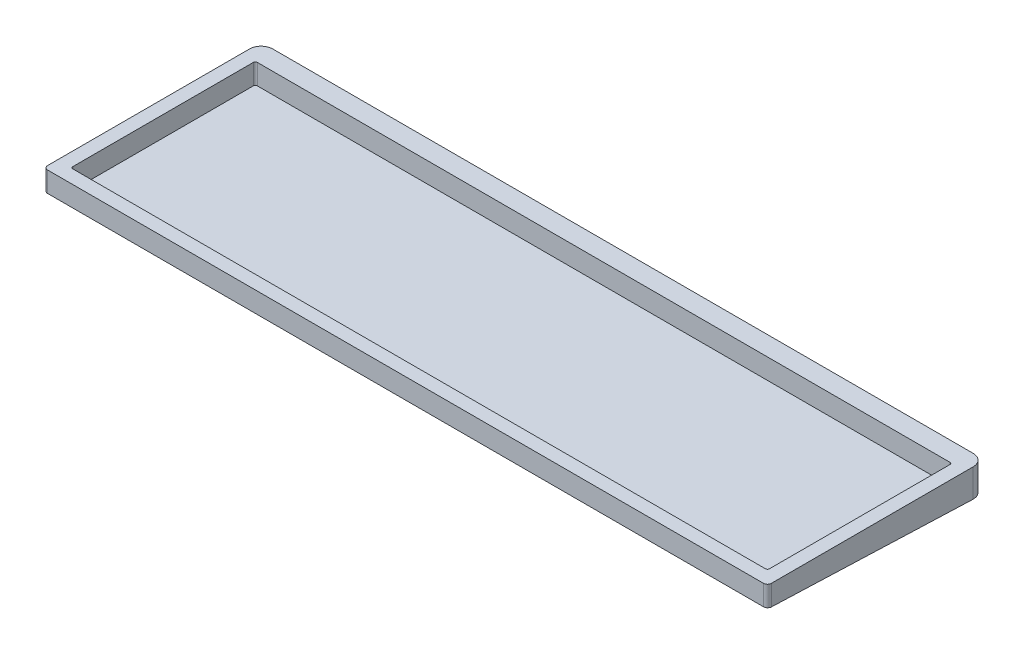
SolidWorks part; units mm, degrees
ref_plane "Front Plane" through (0, 0, 0) normal (0, 0, 1) x (1, 0, 0)
ref_plane "Top Plane" through (0, 0, 0) normal (0, 1, 0) x (1, 0, 0)
ref_plane "Right Plane" through (0, 0, 0) normal (1, 0, 0) x (0, 0, -1)
sketch "Sketch1" plane through (0, 0, 0) normal (0, 1, 0) x (1, 0, 0)
  line L1 (-178.825, 47.625) -> (178.825, 47.625)
  line L2 (-179.825, 46.625) -> (-179.825, -46.625)
  line L3 (-178.825, -47.625) -> (178.825, -47.625)
  line L4 (179.825, 46.625) -> (179.825, -46.625)
  line L5 (-179.825, 47.625) -> (179.825, -47.625) construction
  line L6 (-179.825, -47.625) -> (179.825, 47.625) construction
  arc A0 (178.825, -47.625) -> (179.825, -46.625) centre (178.825, -46.625) ccw
  arc A1 (178.825, 47.625) -> (179.825, 46.625) centre (178.825, 46.625) cw
  arc A2 (-179.825, -46.625) -> (-178.825, -47.625) centre (-178.825, -46.625) ccw
  arc A3 (-178.825, 47.625) -> (-179.825, 46.625) centre (-178.825, 46.625) ccw
  circle A4 centre (157.075, 19.175) radius 1.1
  circle A5 centre (136.925, -16.775) radius 1.1
  circle A6 centre (-153.475, 33.725) radius 1.1
  circle A7 centre (17.925, 22.275) radius 1.1
  circle A8 centre (17.875, -35.075) radius 1.1
  circle A9 centre (-130.375, -35.725) radius 1.1
  point P0 (0, 0)
  dimension "D3" = 1
  dimension "D4" = 2.2
  dimension "D7" = 2.2
  dimension "D8" = 2.2
  dimension "D9" = 2.2
  dimension "D10" = 2.2
  dimension "D11" = 2.2
  dimension "D1" = 359.65
  dimension "D2" = 95.25
  dimension "D5" = 22.75
  dimension "D6" = 28.45
  dimension "D12" = 42.9
  dimension "D13" = 30.85
  dimension "D14" = 25.35
  dimension "D15" = 161.9
  dimension "D16" = 12.55
  dimension "D17" = 161.95
  dimension "D18" = 11.9
  dimension "D19" = 49.45
  dimension "D20" = 13.9
  dimension "D21" = 26.35
sketch "Sketch2" plane through (0, 0, 0) normal (0, 1, 0) x (1, 0, 0)
  line L0 (-179.825, 46.625) -> (-179.825, -46.625) construction
  line L1 (-178.825, -47.625) -> (178.825, -47.625) construction
  line L2 (179.825, 46.625) -> (179.825, -46.625) construction
  line L3 (-178.825, 47.625) -> (178.825, 47.625) construction
  line L4 (-179.825, 46.625) -> (-179.825, -46.625)
  line L5 (-178.825, -47.625) -> (178.825, -47.625)
  line L6 (179.825, 46.625) -> (179.825, -46.625)
  line L7 (-178.825, 47.625) -> (178.825, 47.625)
  line L9 (-180.825, 57.625) -> (180.825, 57.625)
  line L10 (-186.825, 51.625) -> (-186.825, -52.625)
  line L11 (-184.825, -54.625) -> (184.825, -54.625)
  line L12 (186.825, 51.625) -> (186.825, -52.625)
  circle A0 centre (157.075, 19.175) radius 1.1 construction
  circle A1 centre (136.925, -16.775) radius 1.1 construction
  circle A2 centre (17.875, -35.075) radius 1.1 construction
  circle A3 centre (17.925, 22.275) radius 1.1 construction
  circle A4 centre (-153.475, 33.725) radius 1.1 construction
  circle A5 centre (-130.375, -35.725) radius 1.1 construction
  arc A6 (-179.825, -46.625) -> (-178.825, -47.625) centre (-178.825, -46.625) ccw construction
  arc A7 (178.825, -47.625) -> (179.825, -46.625) centre (178.825, -46.625) ccw construction
  arc A8 (179.825, 46.625) -> (178.825, 47.625) centre (178.825, 46.625) ccw construction
  arc A9 (-178.825, 47.625) -> (-179.825, 46.625) centre (-178.825, 46.625) ccw construction
  circle A10 centre (157.075, 19.175) radius 1.1
  circle A11 centre (136.925, -16.775) radius 1.1
  circle A12 centre (17.875, -35.075) radius 1.1
  circle A13 centre (17.925, 22.275) radius 1.1
  circle A14 centre (-153.475, 33.725) radius 1.1
  circle A15 centre (-130.375, -35.725) radius 1.1
  arc A16 (-179.825, -46.625) -> (-178.825, -47.625) centre (-178.825, -46.625) ccw
  arc A17 (178.825, -47.625) -> (179.825, -46.625) centre (178.825, -46.625) ccw
  arc A18 (179.825, 46.625) -> (178.825, 47.625) centre (178.825, 46.625) ccw
  arc A19 (-178.825, 47.625) -> (-179.825, 46.625) centre (-178.825, 46.625) ccw
  arc A20 (180.825, 57.625) -> (186.825, 51.625) centre (180.825, 51.625) cw
  arc A21 (-180.825, 57.625) -> (-186.825, 51.625) centre (-180.825, 51.625) ccw
  arc A22 (184.825, -54.625) -> (186.825, -52.625) centre (184.825, -52.625) ccw
  arc A23 (-186.825, -52.625) -> (-184.825, -54.625) centre (-184.825, -52.625) ccw
  point P30 (0, 0)
  dimension "D5" = 6
  dimension "D6" = 2
  dimension "D1" = 10
  dimension "D2" = 7
  dimension "D3" = 7
  dimension "D4" = 7
extrude "Boss-Extrude1" add sketch "Sketch2" along normal blind 10.5 contours L10 A23 L11 A22 L12 A20 L9 A21 A19 L7 A18 L6 A17 L5 A16 L4
sketch "Sketch4" plane through (0, 0, 0) normal (0, -1, 0) x (1, 0, 0)
  line L0 (186.825, -51.625) -> (186.825, 52.625) construction
  line L1 (-180.825, -57.625) -> (180.825, -57.625) construction
  line L2 (-186.825, -51.625) -> (-186.825, 52.625) construction
  line L3 (-184.825, 54.625) -> (184.825, 54.625) construction
  line L4 (-179.825, 46.625) -> (-179.825, -46.625)
  line L5 (178.825, 47.625) -> (-178.825, 47.625)
  line L6 (179.825, -46.625) -> (179.825, 46.625)
  line L7 (-178.825, -47.625) -> (178.825, -47.625)
  line L8 (-179.825, 46.625) -> (-179.825, -46.625)
  line L10 (179.825, -46.625) -> (179.825, 46.625)
  line L11 (-178.825, -47.625) -> (178.825, -47.625)
  line L12 (186.825, -51.625) -> (186.825, 52.625)
  line L13 (-180.825, -57.625) -> (180.825, -57.625)
  line L14 (-186.825, -51.625) -> (-186.825, 52.625)
  line L15 (-184.825, 54.625) -> (184.825, 54.625)
  arc A0 (186.825, 52.625) -> (184.825, 54.625) centre (184.825, 52.625) ccw construction
  arc A1 (180.825, -57.625) -> (186.825, -51.625) centre (180.825, -51.625) ccw construction
  arc A2 (-186.825, -51.625) -> (-180.825, -57.625) centre (-180.825, -51.625) ccw construction
  arc A3 (-184.825, 54.625) -> (-186.825, 52.625) centre (-184.825, 52.625) ccw construction
  arc A4 (-179.825, -46.625) -> (-178.825, -47.625) centre (-178.825, -46.625) ccw
  arc A5 (-178.825, 47.625) -> (-179.825, 46.625) centre (-178.825, 46.625) ccw
  arc A6 (179.825, 46.625) -> (178.825, 47.625) centre (178.825, 46.625) ccw
  arc A7 (178.825, -47.625) -> (179.825, -46.625) centre (178.825, -46.625) ccw
  arc A8 (-179.825, -46.625) -> (-178.825, -47.625) centre (-178.825, -46.625) ccw
  arc A9 (-178.825, 47.625) -> (-179.825, 46.625) centre (-178.825, 46.625) ccw
  arc A10 (179.825, 46.625) -> (178.825, 47.625) centre (178.825, 46.625) ccw
  arc A11 (178.825, -47.625) -> (179.825, -46.625) centre (178.825, -46.625) ccw
  arc A12 (186.825, 52.625) -> (184.825, 54.625) centre (184.825, 52.625) ccw
  arc A13 (180.825, -57.625) -> (186.825, -51.625) centre (180.825, -51.625) ccw
  arc A14 (-186.825, -51.625) -> (-180.825, -57.625) centre (-180.825, -51.625) ccw
  arc A15 (-184.825, 54.625) -> (-186.825, 52.625) centre (-184.825, 52.625) ccw
  arc M9 (-178.825, -47.625) -> (-179.825, -46.625) centre (-178.825, -46.625) cw
  line M10 (-179.825, -46.625) -> (-179.825, 46.625)
  arc M11 (-179.825, 46.625) -> (-178.825, 47.625) centre (-178.825, 46.625) cw
  line M12 (-178.825, 47.625) -> (178.825, 47.625)
  arc M13 (178.825, 47.625) -> (179.825, 46.625) centre (178.825, 46.625) cw
  line M14 (179.825, 46.625) -> (179.825, -46.625)
  arc M15 (179.825, -46.625) -> (178.825, -47.625) centre (178.825, -46.625) cw
  line M16 (178.825, -47.625) -> (-178.825, -47.625)
  line M17 (-186.825, 52.625) -> (-186.825, -51.625)
  arc M18 (-186.825, -51.625) -> (-180.825, -57.625) centre (-180.825, -51.625) ccw
  line M19 (-180.825, -57.625) -> (180.825, -57.625)
  arc M20 (180.825, -57.625) -> (186.825, -51.625) centre (180.825, -51.625) ccw
  line M21 (186.825, -51.625) -> (186.825, 52.625)
  arc M22 (186.825, 52.625) -> (184.825, 54.625) centre (184.825, 52.625) ccw
  line M23 (184.825, 54.625) -> (-184.825, 54.625)
  arc M24 (-184.825, 54.625) -> (-186.825, 52.625) centre (-184.825, 52.625) ccw
  dimension "D1" = 0
extrude "Boss-Extrude3" add sketch "Sketch4" along normal blind 10.5 contours M24 M17 M18 M19 M20 M21 M22 M23 M16 M9 M10 M11 M12 M13 M14 M15 | M9 M16 M15 M14 M13 M12 M11 M10
sketch "Sketch5" plane through (186.825, 0, 0) normal (1, 0, 0) x (0, 0, -1)
  line L0 (-54.625, 0) -> (57.625, 0) construction
  line L1 (-54.625, 10.5) -> (-54.625, -10.5) construction
  line L2 (57.625, 10.5) -> (57.625, -10.5) construction
  line L4 (57.625, -4) -> (51.625, -4)
  line L14 (40.9479, -10.5) -> (-54.625, 0)
  line L17 (-54.625, 0) -> (-54.625, -10.5)
  line L18 (-54.625, -10.5) -> (40.9479, -10.5)
  line L21 (51.625, -10.5) -> (-52.625, -10.5) construction
  line L22 (51.625, -10.5) -> (40.9479, -10.5)
  line L23 (51.625, 10.5) -> (51.625, -10.5) construction
  line L24 (51.625, -4) -> (40.9479, -10.5)
  line L25 (40.9479, -10.5) -> (57.625, -10.5)
  line L26 (57.625, -10.5) -> (57.625, -4)
  line M5 (-52.625, 10.5) -> (-52.625, -10.5)
  line M6 (-52.625, -10.5) -> (51.625, -10.5)
  line M7 (51.625, -10.5) -> (51.625, 10.5)
  dimension "D1" = 4
  dimension "D2" = 12.5
extrude "Cut-Extrude1" cut sketch "Sketch5" against normal blind 400 contours L17 L18 L14 M5 | L14 M6 M5 | L24 M7 M6 | L25 L26 L4 M7
sketch "Sketch6" plane through (186.825, 0, 0) normal (1, 0, 0) x (0, 0, -1)
  line L4 (-54.625, 0) -> (51.625, -4)
  line L5 (51.625, -4) -> (40.9479, -10.5)
  line L6 (40.9479, -10.5) -> (-54.625, 0)
extrude "Cut-Extrude2" cut sketch "Sketch6" against normal blind 40
sketch "Sketch7" plane through (-186.825, 0, 0) normal (-1, 0, 0) x (0, 0, 1)
  line L4 (-51.625, -4) -> (-40.9479, -10.5)
  line L5 (-40.9479, -10.5) -> (52.625, -0.2197)
  line L6 (52.625, -0.2197) -> (-51.625, -4)
extrude "Cut-Extrude3" cut sketch "Sketch7" against normal blind 40
ref_plane "Plane1" through (0, -10.5, 0) normal (0, 1, 0) x (1, 0, 0)
